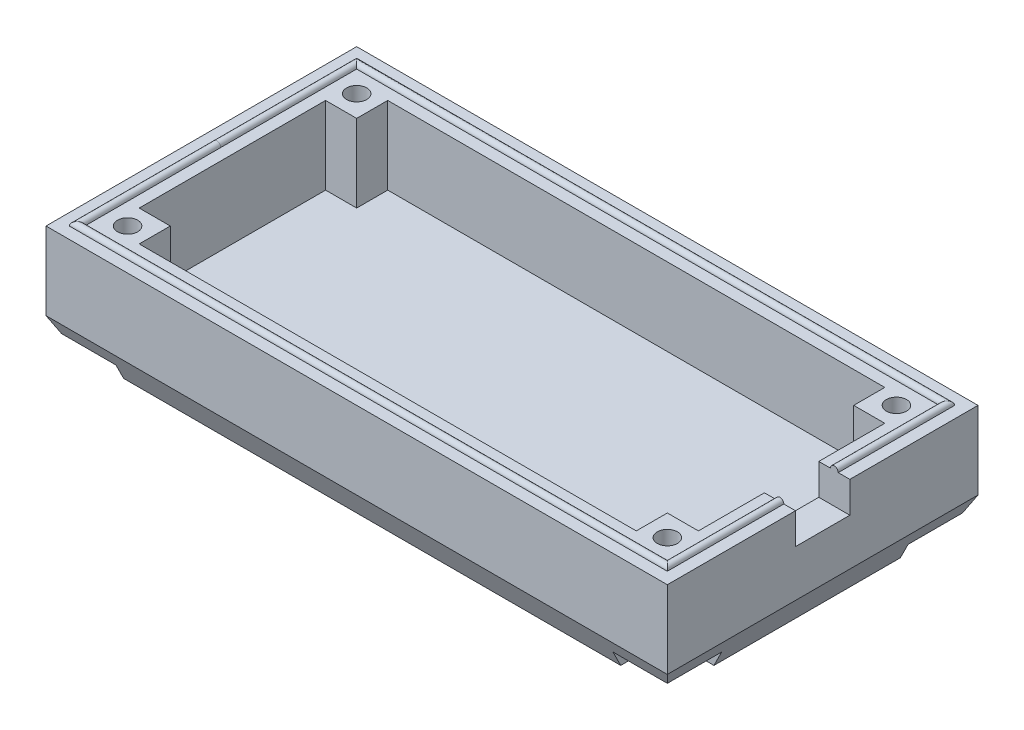
SolidWorks part; units mm, degrees
ref_plane "Piano frontale" through (0, 0, 0) normal (0, 0, 1) x (1, 0, 0)
ref_plane "Piano superiore" through (0, 0, 0) normal (0, 1, 0) x (1, 0, 0)
ref_plane "Piano destro" through (0, 0, 0) normal (1, 0, 0) x (0, 0, -1)
sketch "Schizzo2" plane through (0, 0, 0) normal (0, 1, 0) x (1, 0, 0)
  line L1 (20, -10) -> (-20, -10)
  line L2 (20, -10) -> (20, 10)
  line L3 (20, 10) -> (-20, 10)
  line L4 (-20, -10) -> (-20, 10)
  line L5 (20, -10) -> (-20, 10) construction
  line L6 (20, 10) -> (-20, -10) construction
  point P0 (0, 0)
  dimension "D1" = 40
  dimension "D2" = 20
extrude "Estrusione-Estrusione1" add sketch "Schizzo2" against normal blind 7
sketch "Schizzo3" plane through (0, 0, 0) normal (0, 1, 0) x (1, 0, 0)
  line L0 (20, 10) -> (-20, 10) construction
  line L1 (-16, 8) -> (16, 8)
  line L2 (-18, 6) -> (-18, -6)
  line L3 (-16, -8) -> (16, -8)
  line L4 (18, 6) -> (18, -6)
  line L7 (-18, 6) -> (-16, 6)
  line L8 (-20, 10) -> (-20, -10) construction
  line L9 (-16, 6) -> (-16, 8)
  line L10 (16, -8) -> (16, -6)
  line L11 (16, -6) -> (18, -6)
  line L12 (18, 6) -> (16, 6)
  line L13 (16, 6) -> (16, 8)
  line L14 (-16, -8) -> (-16, -6)
  line L15 (-16, -6) -> (-18, -6)
  point P0 (0, 0)
  dimension "D1" = 2
  dimension "D2" = 2
  dimension "D3" = 2
  dimension "D4" = 12
  dimension "D5" = 32
extrude "Taglio-Estrusione1" cut sketch "Schizzo3" against normal blind 5
sketch "Schizzo4" plane through (0, 0, 0) normal (0, 0, 1) x (1, 0, 0)
  line L0 (-20, 0) -> (20, 0) construction
  line L1 (-18.75, 0) -> (-19.25, 0)
  arc A0 (-18.75, 0) -> (-19.25, 0) centre (-19, 0) ccw
  dimension "D2" = 0.5
  dimension "D1" = 1
sketch "Schizzo5" plane through (0, 0, 0) normal (0, 1, 0) x (1, 0, 0)
  line L0 (-20, 10) -> (-20, -10) construction
  line L1 (19, -9) -> (-19, -9)
  line L2 (19, -9) -> (19, 9)
  line L3 (19, 9) -> (-19, 9)
  line L4 (-19, -9) -> (-19, 9)
  line L5 (19, -9) -> (-19, 9) construction
  line L6 (19, 9) -> (-19, -9) construction
  line L7 (20, 10) -> (-20, 10) construction
  point P0 (0, 0)
  dimension "D1" = 1
  dimension "D2" = 1
sweep "Sweep1" add profiles "Schizzo4" path "Schizzo5"
chamfer "Smusso1" distance 1 distance2 2 4 edges at (0, -7, 10) (20, -7, 0) (0, -7, -10) (-20, -7, 0)
sketch "Schizzo6" plane through (0, -7, 0) normal (0, -1, 0) x (1, 0, 0)
  line L1 (-20, 10) -> (-16, 10)
  line L2 (-20, 10) -> (-20, 6)
  line L3 (-20, 6) -> (-16, 6)
  line L4 (-16, 10) -> (-16, 6)
  line L5 (20, 10) -> (16, 10)
  line L6 (20, 10) -> (20, 6)
  line L7 (20, 6) -> (16, 6)
  line L8 (16, 10) -> (16, 6)
  line L9 (20, -10) -> (16, -10)
  line L10 (20, -10) -> (20, -6)
  line L11 (20, -6) -> (16, -6)
  line L12 (16, -10) -> (16, -6)
  line L13 (-20, -10) -> (-16, -10)
  line L14 (-20, -10) -> (-20, -6)
  line L15 (-20, -6) -> (-16, -6)
  line L16 (-16, -10) -> (-16, -6)
  dimension "D1" = 4
extrude "Taglio-Estrusione2" cut sketch "Schizzo6" against normal blind 1
hole_wizard "Foro per Vite M1-1" positions "Schizzo12" profile "Schizzo13" hole size "M1" standard "ISO" end condition through all
sketch "Schizzo12" plane through (0, -6, 0) normal (0, -1, 0) x (-1, 0, 0)
  line L0 (-20, -10) -> (-20, 10) construction
  line L2 (-20, 10) -> (20, 10) construction
  point P0 (-17.375, 7.375)
  dimension "D1" = 2.625
  dimension "D2" = 2.625
sketch "Schizzo13" plane through (17.375, -6, -7.375) normal (1, 0, 0) x (0, 0, -1)
  line L0 (0, 0) -> (0, 6.25)
  line L1 (0, 6.25) -> (0.65, 6.25)
  line L2 (0.65, 6.25) -> (0.65, 0.025)
  line L3 (0.65, 0.025) -> (0.675, 0)
  line L5 (0.675, 0) -> (0, 0)
  line L6 (-0.65, 0.025) -> (-0.675, 0) construction
  line L11 (0, -6.35) -> (0, 107.95) construction
  dimension "Thru Hole Dia." = 1.3
  dimension "Thru Hole Depth" = 6.25
  dimension "Near C'Sink Dia." = 1.35
  dimension "Near C'Sink Angle" = 90
cosmetic thread "Cosmetic Thread1" parameters "D2"=2.3
mirror "Specchia1" about plane through (0, 0, 0) normal (1, 0, 0) of "Foro per Vite M1-1"
cosmetic thread "Cosmetic Thread2" parameters "D2"=2.3
mirror "Specchia2" about plane through (0, 0, 0) normal (0, 0, 1) of "Specchia1", "Foro per Vite M1-1"
cosmetic thread "Cosmetic Thread3" parameters "D2"=2.3
cosmetic thread "Cosmetic Thread4" parameters "D2"=2.3
sketch "Schizzo14" plane through (20, 0, 0) normal (1, 0, 0) x (0, 0, -1)
  line L1 (-1.75, 2) -> (1.75, 2)
  line L2 (-1.75, 2) -> (-1.75, -2)
  line L3 (-1.75, -2) -> (1.75, -2)
  line L4 (1.75, 2) -> (1.75, -2)
  line L5 (-1.75, 2) -> (1.75, -2) construction
  line L6 (-1.75, -2) -> (1.75, 2) construction
  point P0 (0, 0)
  dimension "D1" = 2
  dimension "D2" = 3.5
extrude "Taglio-Estrusione3" cut sketch "Schizzo14" against normal blind 3 and the other way through all
